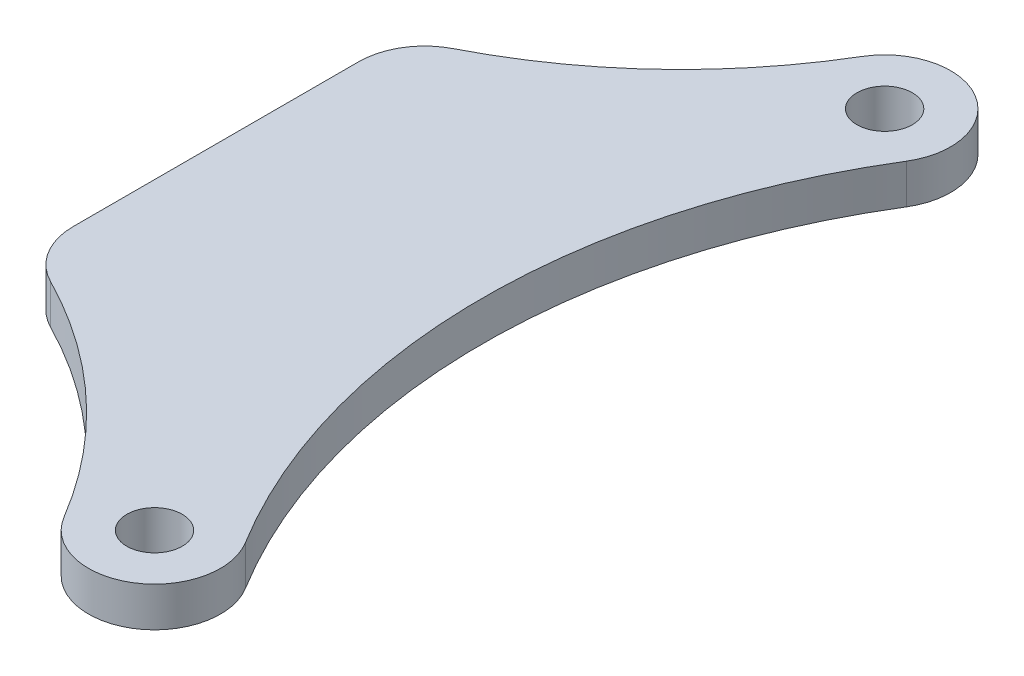
SolidWorks part; units mm, degrees
ref_plane "Front Plane" through (0, 0, 0) normal (0, 0, 1) x (1, 0, 0)
ref_plane "Top Plane" through (0, 0, 0) normal (0, 1, 0) x (1, 0, 0)
ref_plane "Right Plane" through (0, 0, 0) normal (1, 0, 0) x (0, 0, -1)
sketch "Sketch1" plane through (0, 0, 0) normal (0, 1, 0) x (1, 0, 0)
  line L0 (0, -14) -> (0, 14)
  circle A0 centre (23, -27.6464) radius 5
  circle A1 centre (23, 27.6464) radius 2.1
  circle A2 centre (23, -27.6464) radius 2.1
  circle A3 centre (23, 27.6464) radius 5
  arc A4 (18.7031, -30.203) -> (0, -14) centre (-15.0812, -50.3041) ccw
  arc A5 (18.7031, 30.203) -> (0, 14) centre (-15.0812, 50.3041) cw
  arc A6 (27.2602, -25.029) -> (27.2602, 25.029) centre (68, 0) cw
  point P16 (20.186, 0)
  point P18 (0, 0)
extrude "Boss-Extrude1" add sketch "Sketch1" along normal blind 3 contours A0 A6 A3 A5 L0 A4 | A0 A2 | A3 A1
fillet "Fillet1" radius 5 2 edges at (0, 1.5, -14) (0, 1.5, 14)
